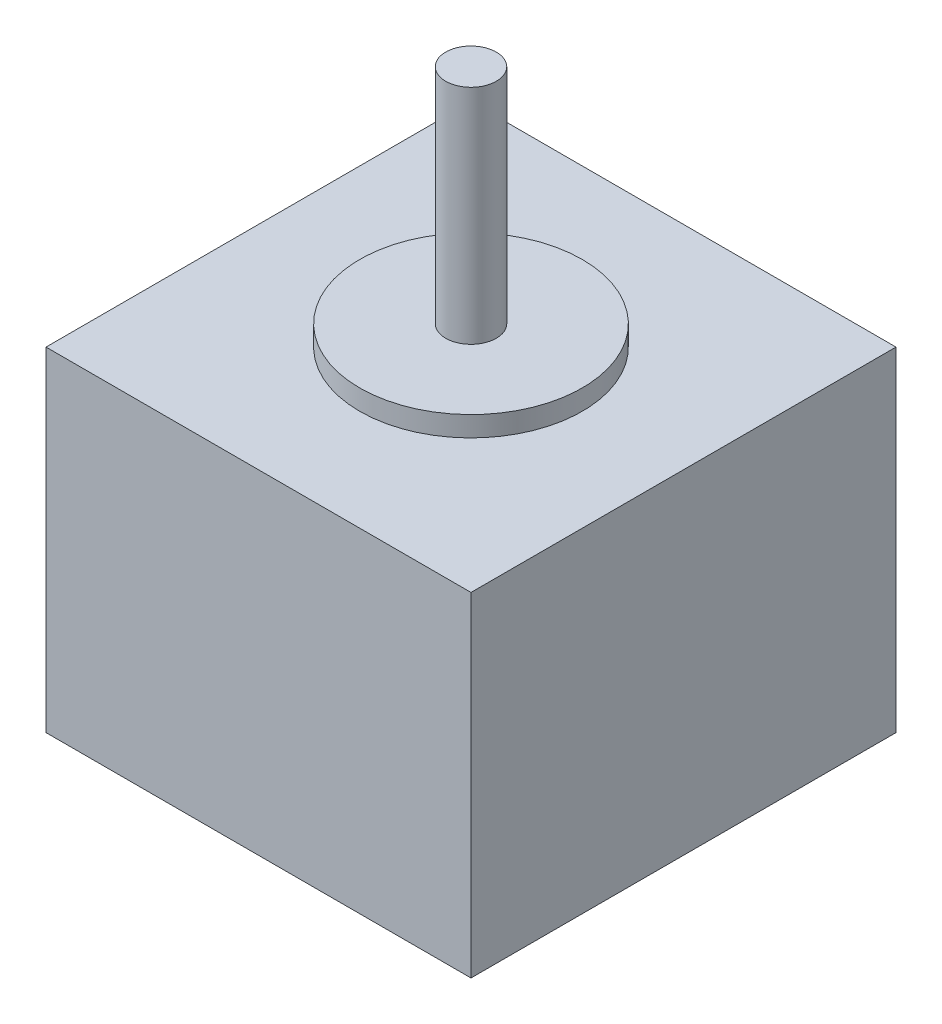
SolidWorks part; units mm, degrees
ref_plane "Front Plane" through (0, 0, 0) normal (0, 0, 1) x (1, 0, 0)
ref_plane "Top Plane" through (0, 0, 0) normal (0, 1, 0) x (1, 0, 0)
ref_plane "Right Plane" through (0, 0, 0) normal (1, 0, 0) x (0, 0, -1)
sketch "Sketch1" plane through (0, 0, 0) normal (0, 1, 0) x (1, 0, 0)
  line L1 (-21, -21) -> (21, -21)
  line L2 (-21, -21) -> (-21, 21)
  line L3 (-21, 21) -> (21, 21)
  line L4 (21, -21) -> (21, 21)
  line L5 (-21, -21) -> (21, 21) construction
  line L6 (-21, 21) -> (21, -21) construction
  point P0 (0, 0)
  dimension "D1" = 42
  dimension "D2" = 42
extrude "Boss-Extrude1" add sketch "Sketch1" along normal blind 33
sketch "Sketch2" plane through (0, 33, 0) normal (0, 1, 0) x (1, 0, 0)
  circle A0 centre (0, 0) radius 11
  dimension "D1" = 22
extrude "Boss-Extrude2" add sketch "Sketch2" along normal blind 2
sketch "Sketch3" plane through (0, 35, 0) normal (0, 1, 0) x (1, 0, 0)
  circle A0 centre (0, 0) radius 2.5
  dimension "D1" = 5
extrude "Boss-Extrude3" add sketch "Sketch3" along normal blind 22
